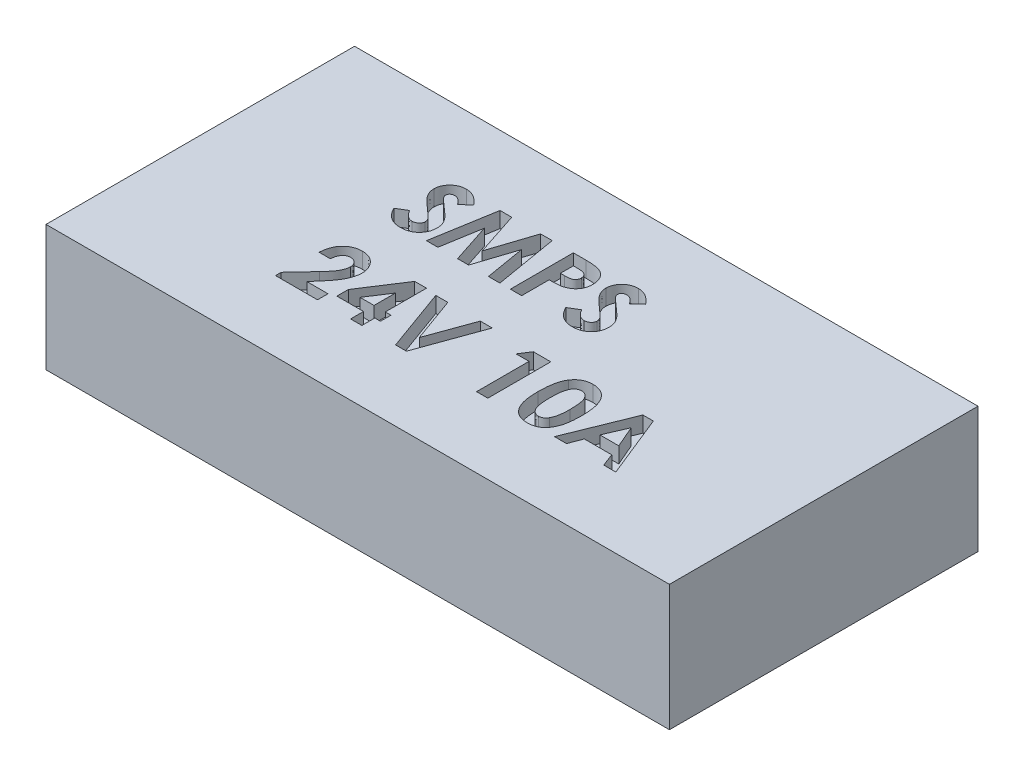
SolidWorks part; units mm, degrees
ref_plane "Ebene vorne" through (0, 0, 0) normal (0, 0, 1) x (1, 0, 0)
ref_plane "Ebene oben" through (0, 0, 0) normal (0, 1, 0) x (1, 0, 0)
ref_plane "Ebene rechts" through (0, 0, 0) normal (1, 0, 0) x (0, 0, -1)
sketch "Skizze1" plane through (0, 0, 0) normal (0, 1, 0) x (1, 0, 0)
  line L1 (-99, 49) -> (99, 49)
  line L2 (-99, 49) -> (-99, -49)
  line L3 (-99, -49) -> (99, -49)
  line L4 (99, 49) -> (99, -49)
  line L5 (-99, 49) -> (99, -49) construction
  line L6 (-99, -49) -> (99, 49) construction
  point P0 (0, 0)
  dimension "D1" = 98
  dimension "D2" = 198
extrude "Aufsatz-Linear austragen1" add sketch "Skizze1" along normal blind 40
sketch "Skizze2" plane through (0, 40, 0) normal (0, 1, 0) x (1, 0, 0)
  text T0 "<b>SMPS</b>\r\n<b>24V 10A</b>" font "Century Gothic" height 20
extrude "Schnitt-Linear austragen1" cut sketch "Skizze2" against normal blind 5
